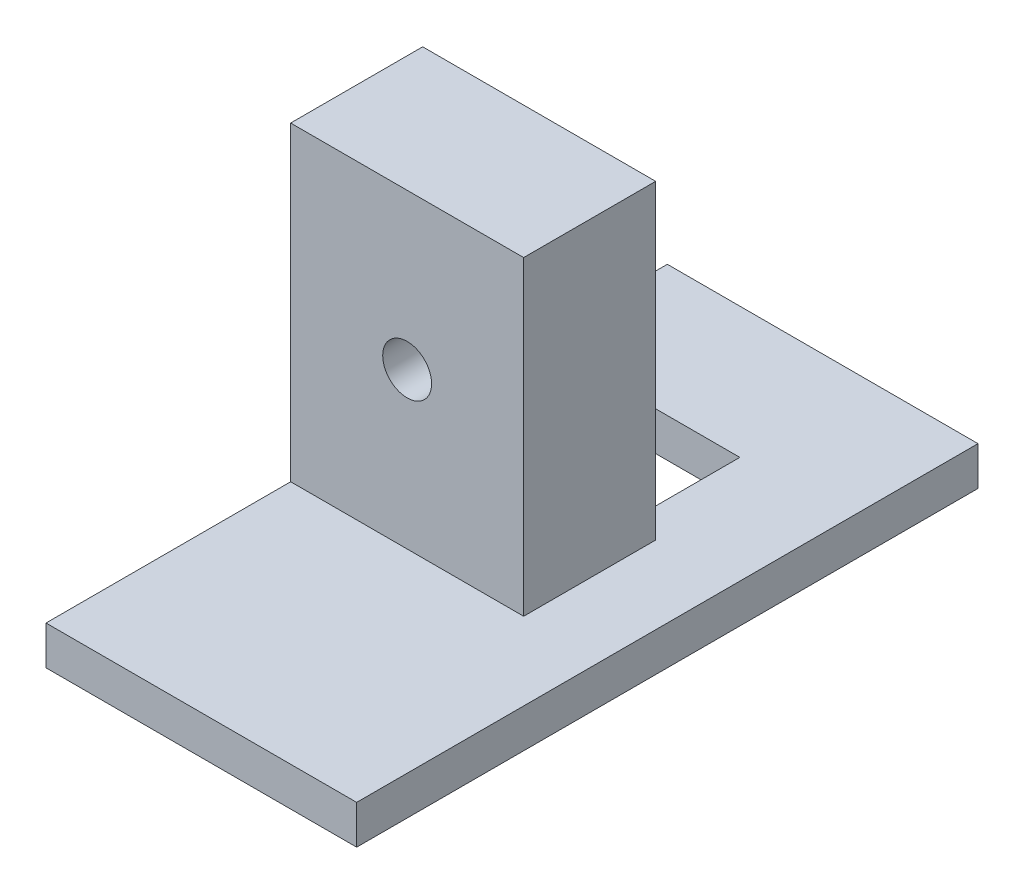
SolidWorks part; units mm, degrees
ref_plane "Front Plane" through (0, 0, 0) normal (0, 0, 1) x (1, 0, 0)
ref_plane "Top Plane" through (0, 0, 0) normal (0, 1, 0) x (1, 0, 0)
ref_plane "Right Plane" through (0, 0, 0) normal (1, 0, 0) x (0, 0, -1)
sketch "Sketch2" plane through (0, 0, 0) normal (0, 1, 0) x (1, 0, 0)
  line L1 (-25.4, -50.8) -> (25.4, -50.8)
  line L2 (-25.4, -50.8) -> (-25.4, 50.8)
  line L3 (-25.4, 50.8) -> (25.4, 50.8)
  line L4 (25.4, -50.8) -> (25.4, 50.8)
  line L5 (-25.4, -50.8) -> (25.4, 50.8) construction
  line L6 (-25.4, 50.8) -> (25.4, -50.8) construction
  point P0 (0, 0)
  dimension "D1" = 101.6
  dimension "D2" = 50.8
extrude "Boss-Extrude1" add sketch "Sketch2" along normal blind 6.35
sketch "Sketch4" plane through (0, 6.35, 0) normal (0, 1, 0) x (1, 0, 0)
  line L1 (12.7, 10.795) -> (-25.4, 10.795)
  line L2 (12.7, 10.795) -> (12.7, -10.795)
  line L3 (12.7, -10.795) -> (-25.4, -10.795)
  line L4 (-25.4, 10.795) -> (-25.4, -10.795)
  dimension "D1" = 21.59
  dimension "D2" = 38.1
  dimension "D3" = 12.7
  dimension "D4" = 10.795
extrude "Boss-Extrude2" add sketch "Sketch4" along normal blind 50.8
sketch "Sketch5" plane through (0, 0, -10.795) normal (0, 0, -1) x (-1, 0, 0)
  line L0 (25.4, 57.15) -> (25.4, 6.35) construction
  line L1 (-12.7, 57.15) -> (25.4, 57.15) construction
  circle A0 centre (6.35, 31.75) radius 4
  dimension "D1" = 8
  dimension "D2" = 19.05
  dimension "D3" = 25.4
extrude "Cut-Extrude1" cut sketch "Sketch5" against normal through all
sketch "Sketch6" plane through (0, 6.35, 0) normal (0, 1, 0) x (1, 0, 0)
  line L0 (12.7, 10.795) -> (-25.4, 10.795) construction
  line L1 (7.874, 13.6652) -> (-20.574, 13.6652)
  line L2 (7.874, 13.6652) -> (7.874, 29.3827)
  line L3 (7.874, 29.3827) -> (-20.574, 29.3827)
  line L4 (-20.574, 13.6652) -> (-20.574, 29.3827)
  line L6 (-25.4, 50.8) -> (-25.4, 10.795) construction
  dimension "D1" = 15.7175
  dimension "D2" = 28.448
  dimension "D3" = 2.8702
  dimension "D4" = 4.826
extrude "Cut-Extrude2" cut sketch "Sketch6" against normal through all
